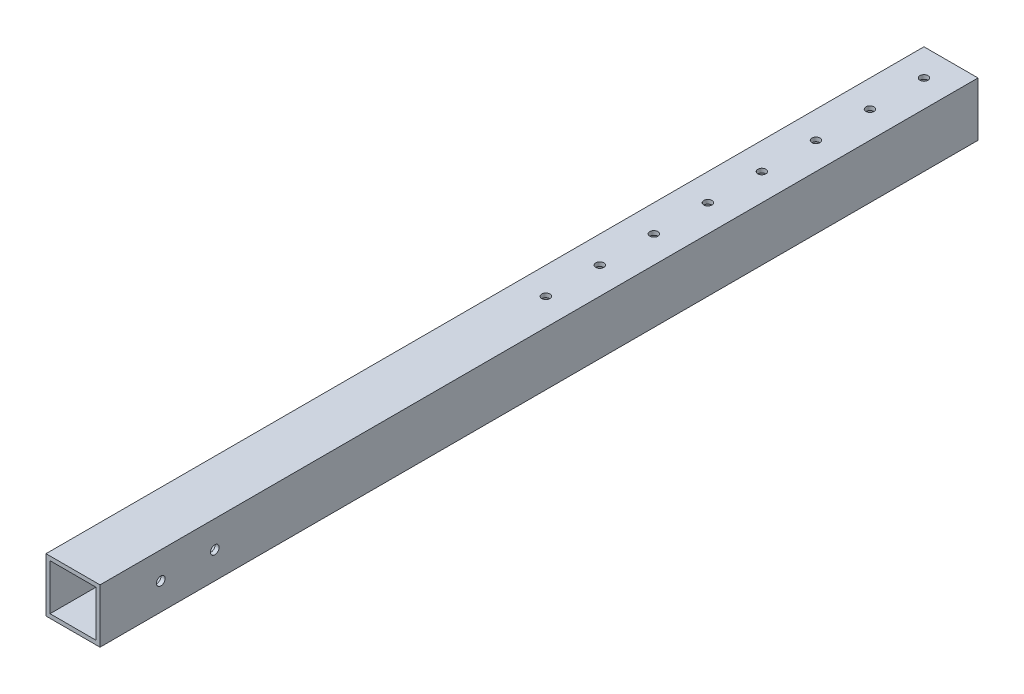
SolidWorks part; units mm, degrees
material "6061 合金"
ref_plane "前视基准面" through (0, 0, 0) normal (0, 0, 1) x (1, 0, 0)
ref_plane "上视基准面" through (0, 0, 0) normal (0, 1, 0) x (1, 0, 0)
ref_plane "右视基准面" through (0, 0, 0) normal (1, 0, 0) x (0, 0, -1)
other "Configuration Table"
sketch "草图1" plane through (0, 0, 0) normal (0, 0, 1) x (1, 0, 0)
  line L1 (-8.5, 8.5) -> (8.5, 8.5)
  line L2 (-8.5, 8.5) -> (-8.5, -8.5)
  line L3 (-8.5, -8.5) -> (8.5, -8.5)
  line L4 (8.5, 8.5) -> (8.5, -8.5)
  line L5 (-8.5, 8.5) -> (8.5, -8.5) construction
  line L6 (-8.5, -8.5) -> (8.5, 8.5) construction
  line L7 (-10, 10) -> (10, 10)
  line L8 (-10, 10) -> (-10, -10)
  line L9 (-10, -10) -> (10, -10)
  line L10 (10, 10) -> (10, -10)
  line L11 (-10, 10) -> (10, -10) construction
  line L12 (-10, -10) -> (10, 10) construction
  point P0 (0, 0)
  point P6 (0, 0)
  dimension "D1" = 20
  dimension "D2" = 20
  dimension "D3" = 1.5
  dimension "D4" = 1.5
extrude "凸台-拉伸1" add sketch "草图1" along normal blind 325.04
sketch "草图2" [suppressed] plane through (0, 10, 0) normal (0, 1, 0) x (1, 0, 0)
  line L0 (0, 0) -> (0, -50000) construction
  line L1 (10, 0) -> (-10, 0) construction
  line L2 (10, -342.12) -> (-10, -342.12) construction
  circle A0 centre (0, -5) radius 1.5
  circle A1 centre (0, -20) radius 1.5
  circle A2 centre (0, -337.12) radius 1.5
  circle A3 centre (0, -322.12) radius 1.5
  dimension "D1" = 5
  dimension "D2" = 15
  dimension "D3" = 3
  dimension "D4" = 5
  dimension "D5" = 15
extrude "切除-拉伸1" [suppressed] cut sketch "草图2" against normal through all
sketch "草图3" [suppressed] plane through (0, 10, 0) normal (0, 1, 0) x (1, 0, 0)
  line L0 (0, 0) -> (0, -50000) construction
  line L1 (0, -35) -> (0, -50) construction
  circle A0 centre (0, -35) radius 1.5
  circle A1 centre (0, -50) radius 1.5
  circle A2 centre (0, -65) radius 1.5
  circle A3 centre (0, -80) radius 1.5
  circle A4 centre (0, -95) radius 1.5
  circle A5 centre (0, -110) radius 1.5
  circle A6 centre (0, -125) radius 1.5
  circle A7 centre (0, -140) radius 1.5
  circle A8 centre (0, -155) radius 1.5
  circle A9 centre (0, -170) radius 1.5
  circle A10 centre (0, -185) radius 1.5
  circle A11 centre (0, -200) radius 1.5
  circle A12 centre (0, -215) radius 1.5
  circle A13 centre (0, -230) radius 1.5
  circle A14 centre (0, -245) radius 1.5
  circle A15 centre (0, -260) radius 1.5
  circle A16 centre (0, -275) radius 1.5
  circle A17 centre (0, -290) radius 1.5
  circle A18 centre (0, -305) radius 1.5
  circle A19 centre (0, -20) radius 1.5 construction
  dimension "D3" = 3
  dimension "D4" = 15
  dimension "D2" = 15
  dimension "D1" = 19
extrude "切除-拉伸2" [suppressed] cut sketch "草图3" against normal through all
sketch "草图4" plane through (-10, 0, 0) normal (-1, 0, 0) x (0, 0, 1)
  line L0 (235.04, 0) -> (-49764.96, 0) construction
  line L1 (325.04, 10) -> (325.04, -10) construction
  circle A0 centre (282.54, 0) radius 1.6
  circle A1 centre (302.54, 0) radius 1.6
  point P11 (325.04, 0)
  dimension "D1" = 3.2
  dimension "D2" = 20
  dimension "D3" = 22.5
extrude "切除-拉伸3" cut sketch "草图4" against normal through all
sketch "草图5" [suppressed] plane through (0, -10, 0) normal (0, -1, 0) x (1, 0, 0)
  line L0 (0, 0) -> (0, -50000) construction
  line L1 (-10, 0) -> (10, 0) construction
  line L2 (0, 10) -> (0, 30) construction
  circle A0 centre (0, 10) radius 1.6
  circle A1 centre (0, 30) radius 1.6
  circle A2 centre (0, 50) radius 1.6
  circle A3 centre (0, 70) radius 1.6
  circle A4 centre (0, 90) radius 1.6
  circle A5 centre (0, 110) radius 1.6
  circle A6 centre (0, 130) radius 1.6
  circle A7 centre (0, 150) radius 1.6
  circle A8 centre (0, 170) radius 1.6
  circle A9 centre (0, 190) radius 1.6
  circle A10 centre (0, 210) radius 1.6
  circle A11 centre (0, 230) radius 1.6
  dimension "D1" = 10
  dimension "D2" = 3.2
  dimension "D4" = 20
  dimension "D3" = 12
extrude "切除-拉伸4" [suppressed] cut sketch "草图5" against normal through all
sketch "草图6" plane through (0, 10, 0) normal (0, 1, 0) x (1, 0, 0)
  line L0 (0, 0) -> (0, -50000) construction
  line L1 (10, 0) -> (-10, 0) construction
  line L2 (0, -10) -> (0, -30) construction
  circle A0 centre (0, -10) radius 1.5
  circle A1 centre (0, -30) radius 1.5
  circle A2 centre (0, -50) radius 1.5
  circle A3 centre (0, -70) radius 1.5
  circle A4 centre (0, -90) radius 1.5
  circle A5 centre (0, -110) radius 1.5
  circle A6 centre (0, -130) radius 1.5
  circle A7 centre (0, -150) radius 1.5
  dimension "D1" = 3
  dimension "D2" = 10
  dimension "D4" = 20
  dimension "D3" = 8
extrude "切除-拉伸5" cut sketch "草图6" against normal through all
